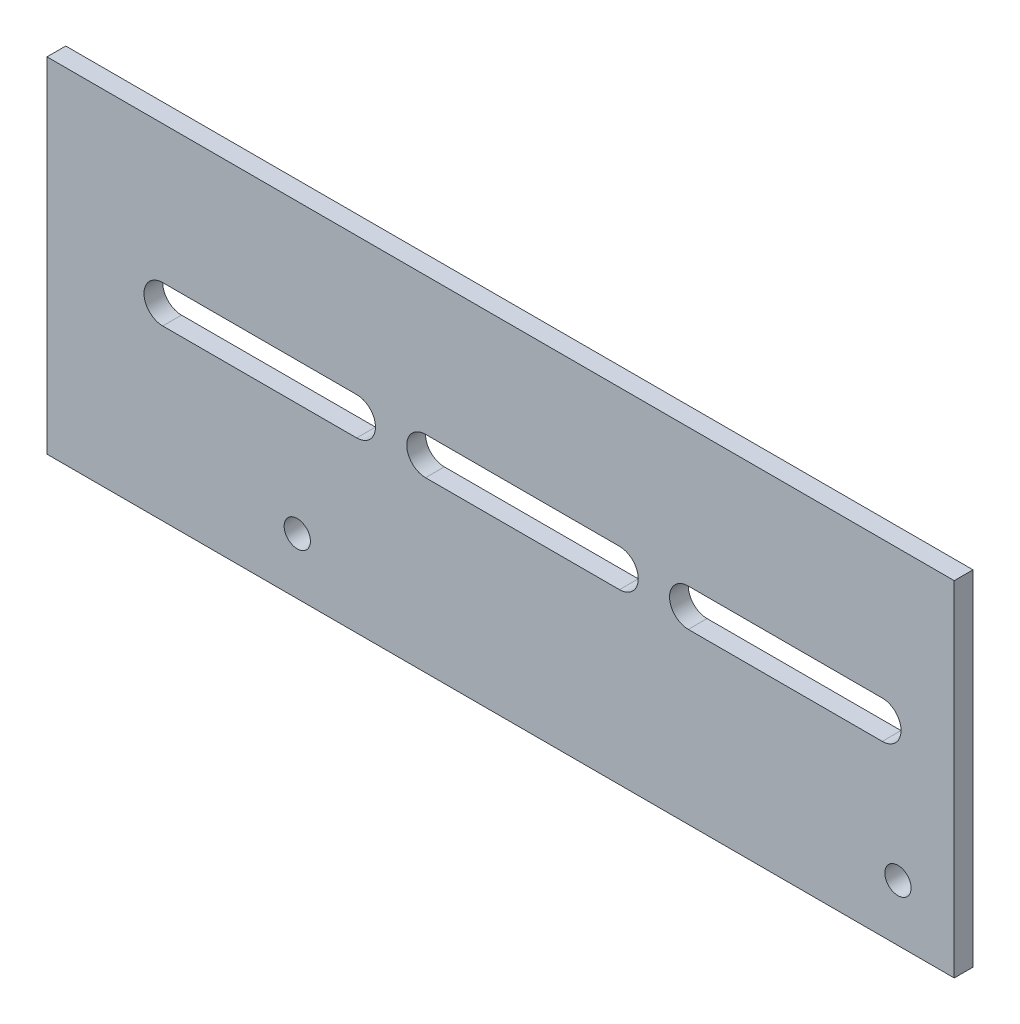
SolidWorks part; units mm, degrees
ref_plane "Front Plane" through (0, 0, 0) normal (0, 0, 1) x (1, 0, 0)
ref_plane "Top Plane" through (0, 0, 0) normal (0, 1, 0) x (1, 0, 0)
ref_plane "Right Plane" through (0, 0, 0) normal (1, 0, 0) x (0, 0, -1)
sketch "Vented lid riser profile" plane through (0, 0, 0) normal (0, 0, 1) x (1, 0, 0)
  line L0 (-91, 52) -> (54, 52)
  line L1 (54, 52) -> (54, 107)
  line L2 (54, 107) -> (-91, 107)
  line L3 (-91, 107) -> (-91, 52)
  line L4 (-72.5, 79) -> (-41.5, 79)
  line L5 (-41.5, 85) -> (-72.5, 85)
  line L6 (-30.5, 79) -> (0.5, 79)
  line L7 (0.5, 85) -> (-30.5, 85)
  line L8 (11.5, 79) -> (42.5, 79)
  line L9 (42.5, 85) -> (11.5, 85)
  circle A0 centre (-51, 61) radius 2.1
  circle A1 centre (45, 61) radius 2.1
  arc A2 (-41.5, 79) -> (-41.5, 85) centre (-41.5, 82) ccw
  arc A3 (-72.5, 85) -> (-72.5, 79) centre (-72.5, 82) ccw
  arc A4 (0.5, 79) -> (0.5, 85) centre (0.5, 82) ccw
  arc A5 (-30.5, 85) -> (-30.5, 79) centre (-30.5, 82) ccw
  arc A6 (42.5, 79) -> (42.5, 85) centre (42.5, 82) ccw
  arc A7 (11.5, 85) -> (11.5, 79) centre (11.5, 82) ccw
extrude "Vented lid riser" add sketch "Vented lid riser profile" along normal blind 3
